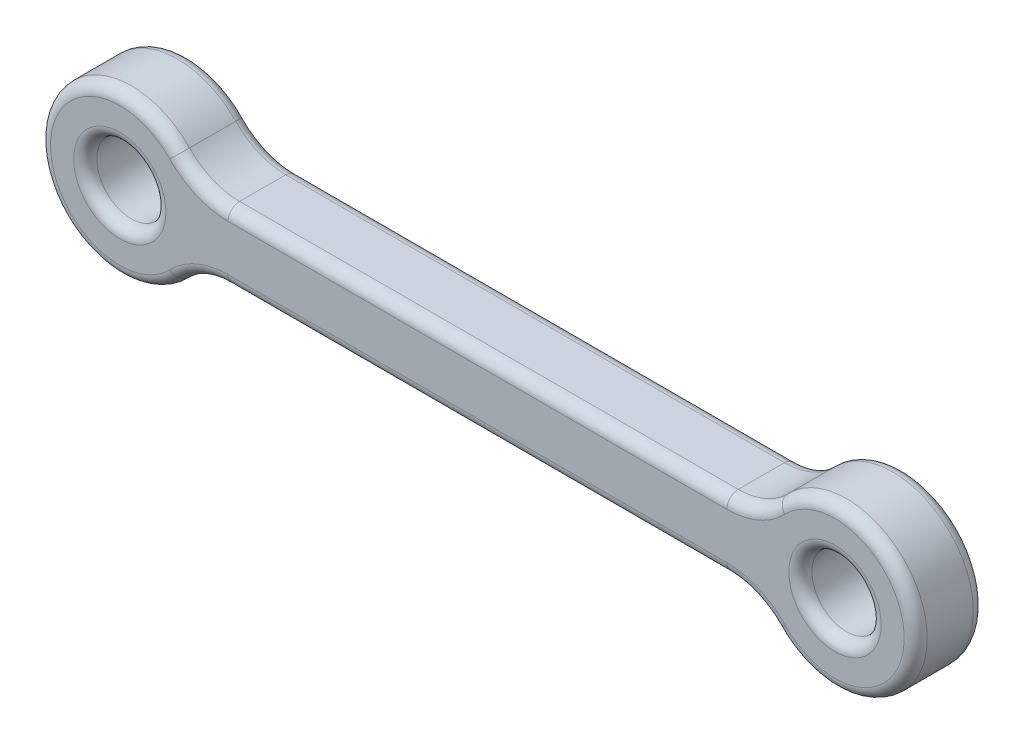
SolidWorks part; units mm, degrees
ref_plane "Front Plane" through (0, 0, 0) normal (0, 0, 1) x (1, 0, 0)
ref_plane "Top Plane" through (0, 0, 0) normal (0, 1, 0) x (1, 0, 0)
ref_plane "Right Plane" through (0, 0, 0) normal (1, 0, 0) x (0, 0, -1)
sketch "Sketch1" plane through (0, 0, 0) normal (0, 0, 1) x (1, 0, 0)
  line L0 (0, 14.0682) -> (0, -13.1713) construction
  line L1 (-12.5727, 0) -> (34.5, 0) construction
  line L2 (4.6904, 1.5) -> (26.3096, 1.5)
  line L3 (4.6904, -1.5) -> (26.3096, -1.5)
  line L4 (16.2641, 6.677) -> (16.2641, -8.0775) construction
  circle A0 centre (0, 0) radius 1.5
  arc A1 (2.5256, 2.4231) -> (2.5256, -2.4231) centre (0, 0) ccw
  circle A2 centre (31, 0) radius 1.5
  arc A4 (2.5256, 2.4231) -> (4.6904, 1.5) centre (4.6904, 4.5) ccw
  arc A5 (2.5256, -2.4231) -> (4.6904, -1.5) centre (4.6904, -4.5) cw
  arc A6 (26.3096, 1.5) -> (28.4744, 2.4231) centre (26.3096, 4.5) ccw
  arc A7 (26.3096, -1.5) -> (28.4744, -2.4231) centre (26.3096, -4.5) cw
  arc A8 (28.4744, -2.4231) -> (28.4744, 2.4231) centre (31, 0) ccw
  dimension "D1" = 31
  dimension "D2" = 7
  dimension "D3" = 3
  dimension "D5" = 6
  dimension "D6" = 6
  dimension "D4" = 1.5
extrude "Boss-Extrude1" add sketch "Sketch1" against normal blind 3
fillet "Fillet1" radius 0.5 19 edges at (27.4863, 1.7404, -3) (34.5, 0, -3) (27.4863, -1.7404, -3) (15.5, -1.5, -3) (3.5137, -1.7404, -3) (-3.5, 0, -3) (3.5137, 1.7404, -3) (27.4863, 1.7404, 0) (34.5, 0, 0) (27.4863, -1.7404, 0) (15.5, -1.5, 0) (3.5137, -1.7404, 0) (-3.5, 0, 0) (3.5137, 1.7404, 0) (1.5, 0, 0) (32.5, 0, -3) (32.5, 0, 0) (15.5, 1.5, -3) (15.5, 1.5, 0)
